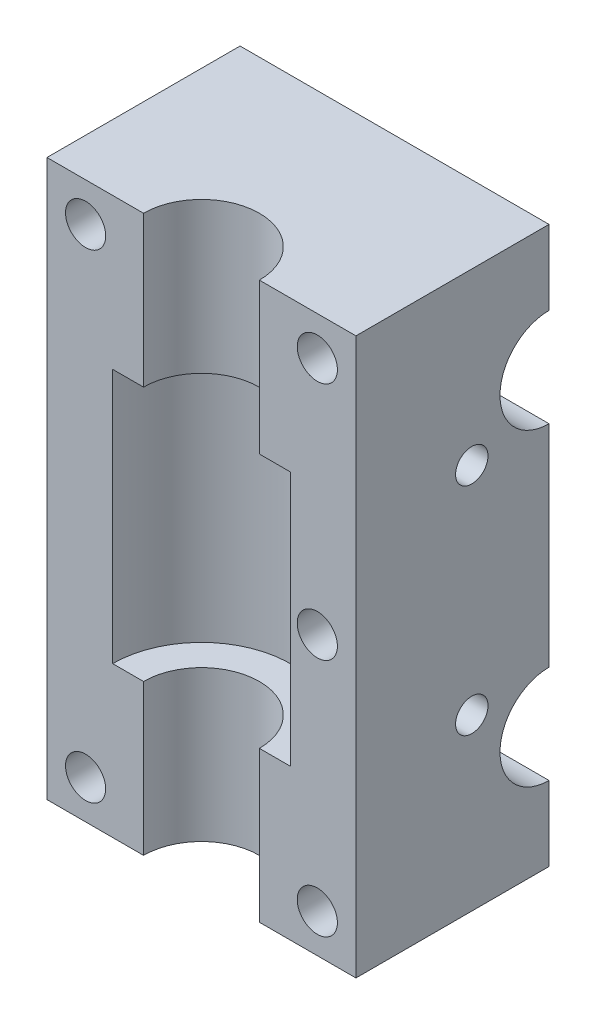
SolidWorks part; units mm, degrees
ref_plane "Front Plane" through (0, 0, 0) normal (0, 0, 1) x (1, 0, 0)
ref_plane "Top Plane" through (0, 0, 0) normal (0, 1, 0) x (1, 0, 0)
ref_plane "Right Plane" through (0, 0, 0) normal (1, 0, 0) x (0, 0, -1)
sketch "Sketch1" plane through (0, 0, 0) normal (0, 1, 0) x (1, 0, 0)
  line L0 (27.5, 0) -> (40, 0)
  line L1 (0, 0) -> (12.5, 0)
  line L2 (0, 0) -> (0, 25)
  line L3 (0, 25) -> (40, 25)
  line L4 (40, 0) -> (40, 25)
  arc A0 (27.5, 0) -> (12.5, 0) centre (20, 0) ccw
  dimension "D3" = 15
  dimension "D1" = 40
  dimension "D2" = 25
  dimension "D4" = 20
  dimension "D5" = 0
extrude "Boss-Extrude1" add sketch "Sketch1" along normal mid plane 72
sketch "Sketch2" plane through (0, 0, 0) normal (0, 1, 0) x (1, 0, 0)
  line L0 (27.5, 0) -> (40, 0) construction
  line L1 (8.5, 0) -> (31.5, 0)
  arc A0 (31.5, 0) -> (8.5, 0) centre (20, 0) ccw
  arc A1 (27.5, 0) -> (12.5, 0) centre (20, 0) ccw construction
  dimension "D1" = 23
  dimension "D2" = 0
  dimension "D3" = 0
extrude "Cut-Extrude1" cut sketch "Sketch2" against normal mid plane 33
sketch "Sketch3" plane through (40, 0, 0) normal (1, 0, 0) x (0, 0, -1)
  line L0 (25, 36) -> (25, -36) construction
  line L1 (0, 36) -> (25, 36) construction
  line L2 (25, 26.35) -> (25, 13.65)
  line L3 (25, -13.65) -> (25, -26.35)
  arc A0 (25, 26.35) -> (25, 13.65) centre (25, 20) ccw
  arc A1 (25, -13.65) -> (25, -26.35) centre (25, -20) ccw
  dimension "D1" = 12.7
  dimension "D3" = 12.7
  dimension "D2" = 0
  dimension "D4" = 40
  dimension "D5" = 16
extrude "Cut-Extrude2" cut sketch "Sketch3" against normal blind 10
sketch "Sketch4" plane through (40, 0, 0) normal (1, 0, 0) x (0, 0, -1)
  line L0 (0, 36) -> (25, 36) construction
  line L1 (25, 13.65) -> (25, -13.65) construction
  circle A0 centre (15, 14) radius 2.1
  circle A1 centre (15, -14) radius 2.1
  dimension "D1" = 4.2
  dimension "D2" = 4.2
  dimension "D3" = 28
  dimension "D4" = 22
  dimension "D5" = 10
  dimension "D6" = 10
extrude "Cut-Extrude3" cut sketch "Sketch4" against normal through all
sketch "Sketch5" plane through (0, 0, 0) normal (0, 0, 1) x (1, 0, 0)
  line L0 (0, 36) -> (0, -36) construction
  line L1 (0, 36) -> (12.5, 36) construction
  line L2 (27.5, 36) -> (40, 36) construction
  line L3 (40, 36) -> (40, -36) construction
  line L4 (0, -36) -> (12.5, -36) construction
  line L5 (27.5, -36) -> (40, -36) construction
  circle A0 centre (5, 31) radius 2.6
  circle A1 centre (35, 31) radius 2.6
  circle A2 centre (35, -31) radius 2.6
  circle A3 centre (5, -31) radius 2.6
  circle A4 centre (35, 0) radius 2.6
  point P22 (0, 0)
  dimension "D1" = 5.2
  dimension "D2" = 5.2
  dimension "D3" = 5.2
  dimension "D4" = 5.2
  dimension "D13" = 5.2
  dimension "D5" = 5
  dimension "D6" = 5
  dimension "D7" = 5
  dimension "D8" = 5
  dimension "D9" = 5
  dimension "D10" = 5
  dimension "D11" = 5
  dimension "D12" = 5
  dimension "D14" = 5
  dimension "D15" = 0
extrude "Cut-Extrude4" cut sketch "Sketch5" against normal through all
equation "\"D4@Sketch1\"=\"D1@Sketch1\"/2"
equation "\"D2@Sketch5\"=\"D1@Sketch5\""
equation "\"D3@Sketch5\"=\"D1@Sketch5\""
equation "\"D4@Sketch5\"=\"D1@Sketch5\""
equation "\"D6@Sketch5\"=\"D5@Sketch5\""
equation "\"D7@Sketch5\"=\"D5@Sketch5\""
equation "\"D8@Sketch5\"=\"D5@Sketch5\""
equation "\"D9@Sketch5\"=\"D5@Sketch5\""
equation "\"D10@Sketch5\"=\"D5@Sketch5\""
equation "\"D11@Sketch5\"=\"D5@Sketch5\""
equation "\"D12@Sketch5\"=\"D5@Sketch5\""
equation "\"D13@Sketch5\"=\"D1@Sketch5\""
equation "\"D14@Sketch5\"=\"D5@Sketch5\""
